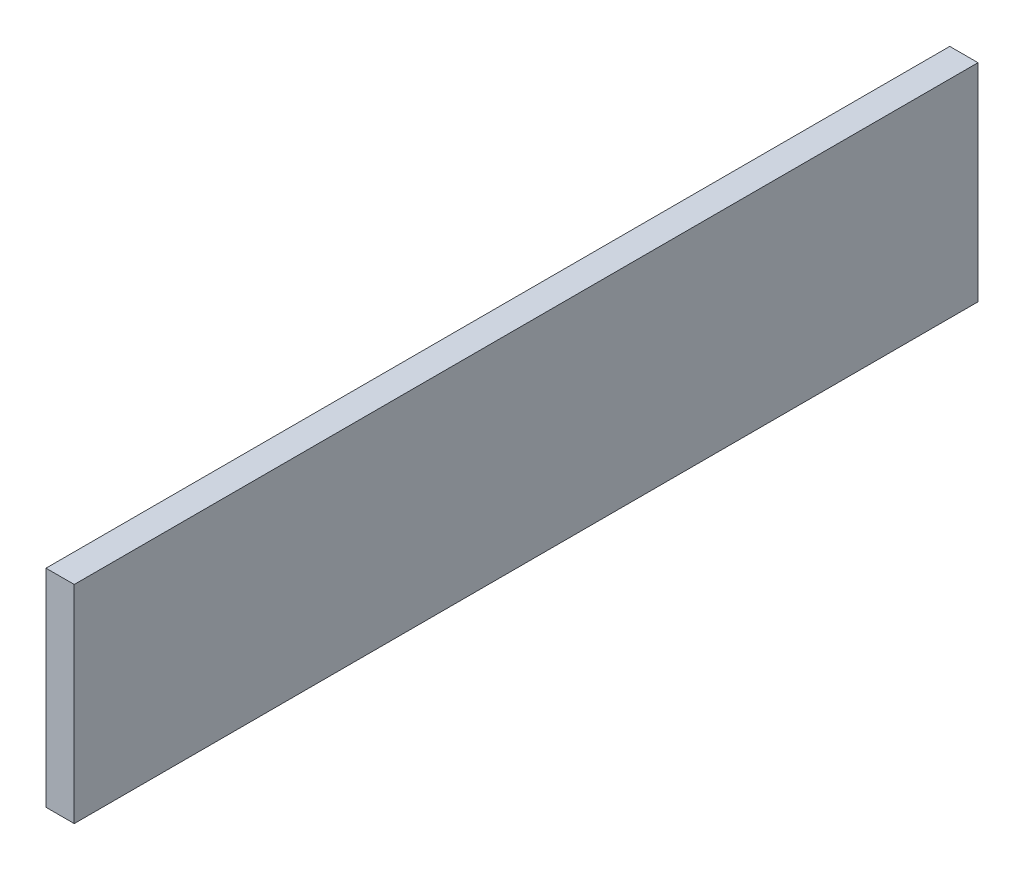
SolidWorks part; units mm, degrees
ref_plane "Front" through (0, 0, 0) normal (0, 0, 1) x (1, 0, 0)
ref_plane "Top" through (0, 0, 0) normal (0, 1, 0) x (1, 0, 0)
ref_plane "Right" through (0, 0, 0) normal (1, 0, 0) x (0, 0, -1)
sketch "Sketch1" plane through (0, 0, 0) normal (1, 0, 0) x (0, 0, -1)
  line L1 (0, 0) -> (609.6, 0)
  line L2 (0, 0) -> (0, 139.7)
  line L3 (0, 139.7) -> (609.6, 139.7)
  line L4 (609.6, 0) -> (609.6, 139.7)
  dimension "D1" = 609.6
  dimension "D2" = 139.7
extrude "Boss-Extrude1" add sketch "Sketch1" along normal blind 19.05
